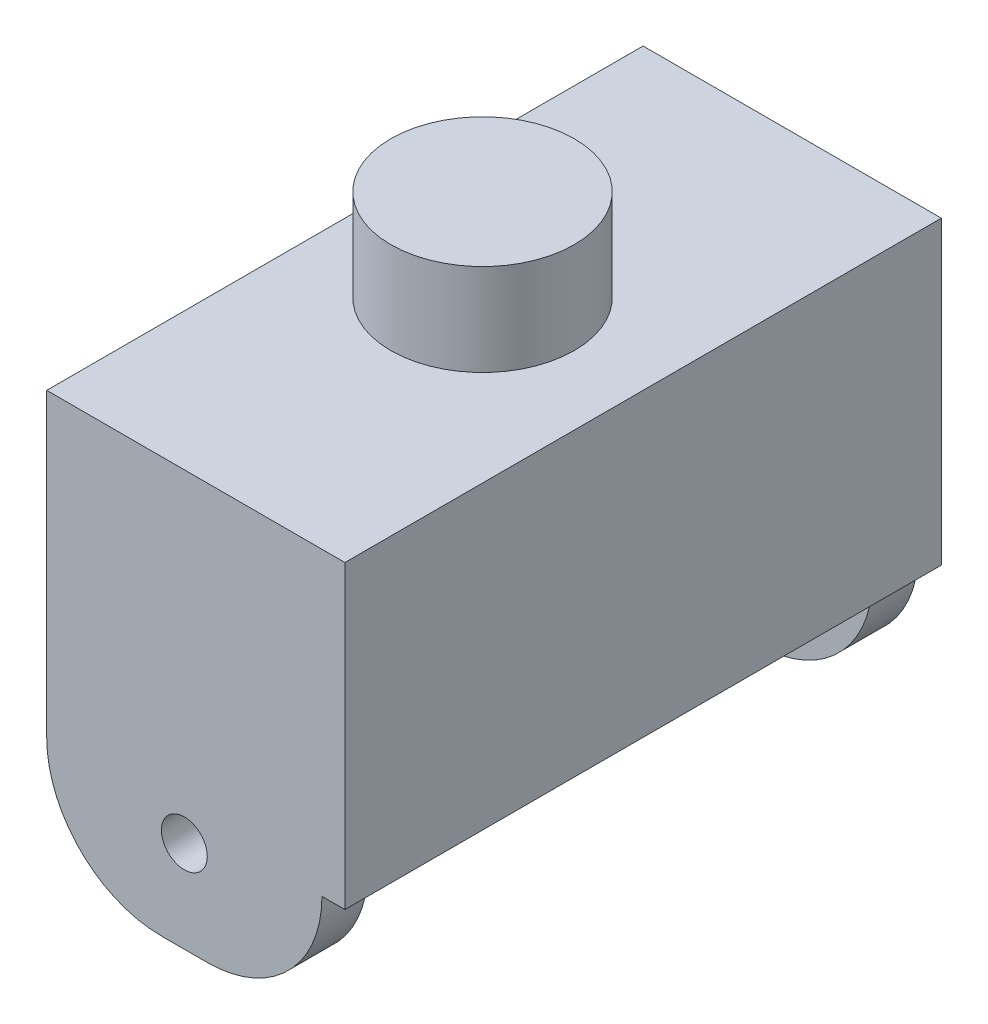
SolidWorks part; units mm, degrees
ref_plane "Front Plane" through (0, 0, 0) normal (0, 0, 1) x (1, 0, 0)
ref_plane "Top Plane" through (0, 0, 0) normal (0, 1, 0) x (1, 0, 0)
ref_plane "Right Plane" through (0, 0, 0) normal (1, 0, 0) x (0, 0, -1)
sketch "Sketch1" plane through (0, 0, 0) normal (0, 0, 1) x (1, 0, 0)
  line L0 (0, 60.184) -> (0, -61.6739) construction
  line L1 (99.6972, 0) -> (-104.9476, 0) construction
  line L6 (-30, 40.5119) -> (30, 40.5119)
  line L7 (-30, 40.5119) -> (-30, -25)
  line L8 (-5, -50) -> (5, -50)
  line L9 (30, 40.5119) -> (30, -25)
  arc A0 (5, -50) -> (30, -25) centre (5, -25) ccw
  arc A1 (-30, -25) -> (-5, -50) centre (-5, -25) ccw
  circle A2 centre (0, -30) radius 5
  point P15 (0, 0)
  point P16 (0, 0)
  point P17 (0, 0)
  point P18 (0, 0)
  point P19 (0, -50)
  dimension "D4" = 25
  dimension "D5" = 20
  dimension "D1" = 60
  dimension "D2" = 30
  dimension "D3" = 50
extrude "Boss-Extrude1" add sketch "Sketch1" along normal blind 10
sketch "Sketch2" plane through (0, 0, 0) normal (0, 0, -1) x (-1, 0, 0)
  line L0 (-30, 40.5119) -> (-30, -25)
  line L1 (-30, -25) -> (-25, -25)
  line L5 (0, 66.4824) -> (0, -63.0582) construction
  line L15 (30, 40.5119) -> (30, -25) construction
  line L16 (30, 30.5119) -> (-25, 30.5119)
  line L17 (-25, 30.5119) -> (-25, -25)
  line L19 (-30, 40.5119) -> (30, 40.5119)
  line L20 (30, 30.5119) -> (30, 40.5119)
  dimension "D1" = 5
  dimension "D2" = 10
extrude "Boss-Extrude2" add sketch "Sketch2" along normal blind 55
mirror "Mirror1" about plane through (0, 0, -55) normal (0, 0, -1) of "Boss-Extrude2", "Boss-Extrude1"
sketch "Sketch3" plane through (0, 40.5119, 0) normal (0, 1, 0) x (1, 0, 0)
  line L0 (0, 127.1219) -> (0, -22.7674) construction
  line L1 (30, -10) -> (-30, -10) construction
  line L2 (-30, -10) -> (-30, 120) construction
  circle A0 centre (0, 55) radius 20
  dimension "D1" = 65
extrude "Boss-Extrude3" add sketch "Sketch3" along normal blind 20
sketch "Sketch4" plane through (30, 0, 0) normal (1, 0, 0) x (0, 0, -1)
  line L0 (-10, 40.5119) -> (120, 40.5119)
  line L1 (120, 40.5119) -> (120, -25)
  line L2 (120, -25) -> (-10, -25)
  line L3 (-10, -25) -> (-10, 40.5119)
extrude "Boss-Extrude4" add sketch "Sketch4" along normal blind 5
